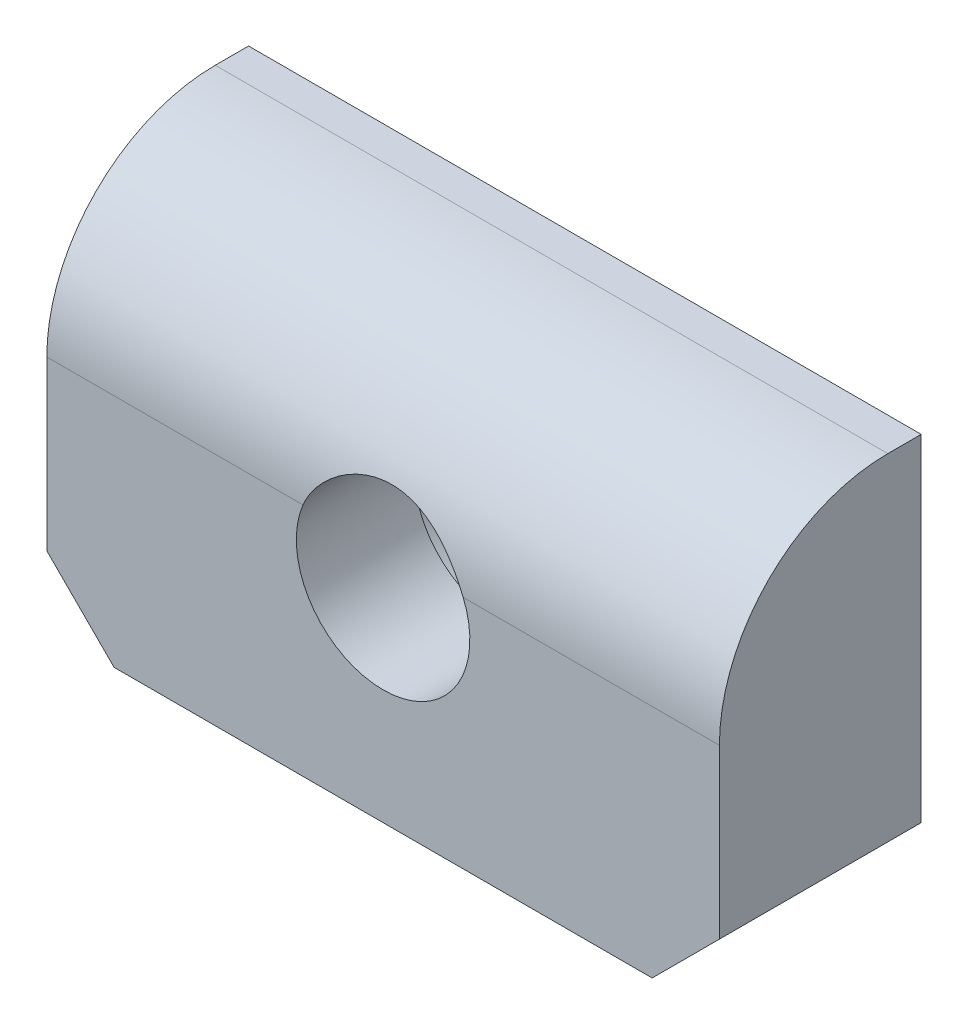
SolidWorks part; units mm, degrees
material "ASTM A36 Steel"
ref_plane "Front Plane" through (0, 0, 0) normal (0, 0, 1) x (1, 0, 0)
ref_plane "Top Plane" through (0, 0, 0) normal (0, 1, 0) x (1, 0, 0)
ref_plane "Right Plane" through (0, 0, 0) normal (1, 0, 0) x (0, 0, -1)
sketch "Sketch3" plane through (0, 0, 0) normal (1, 0, 0) x (0, 0, -1)
  line L0 (-4.7625, 1.5748) -> (-4.7625, -9.525)
  line L1 (-4.7625, -9.525) -> (4.7625, -9.525)
  line L4 (4.7625, 9.525) -> (3.1877, 9.525)
  line L6 (4.7625, 9.525) -> (4.7625, -9.525)
  line L7 (-4.7625, 0) -> (4.7625, 0) construction
  line L8 (0, -9.525) -> (0, 9.525) construction
  arc A0 (3.1877, 9.525) -> (-4.7625, 1.5748) centre (3.1877, 1.5748) ccw
  point P0 (4.7625, -9.2194)
  dimension "D1" = 9.525
  dimension "D5" = 7.9502
  dimension "D6" = 19.05
extrude "Boss-Extrude2" add sketch "Sketch3" along normal mid plane 31.75 contours L0 L1 L4
chamfer "Chamfer1" distance 3.175 angle 45 2 edges at (-15.875, -9.525, 0) (15.875, -9.525, 0)
sketch "Sketch4" plane through (0, 0, 0) normal (1, 0, 0) x (0, 0, -1)
  line L0 (-4.7625, 4.0957) -> (0.8001, 4.0957)
  line L1 (4.7625, -9.525) -> (-4.7625, -9.525) construction
  line L2 (0.8001, 4.0957) -> (0.8001, 5.6769)
  line L3 (0.8001, 5.6769) -> (4.7625, 5.6769)
  line L4 (4.7625, 5.6769) -> (4.7625, 0)
  line L6 (-4.7625, 0) -> (-4.7625, 4.0957)
  line L7 (-4.7625, 0) -> (4.7625, 0)
  line L8 (4.7625, -6.35) -> (4.7625, 9.525) construction
  line L9 (4.7625, 0) -> (4.7625, -5.6769) construction
  line L10 (4.7625, -6.35) -> (4.7625, -9.525) construction
  line L11 (-4.7625, 0) -> (-4.7625, -4.0958) construction
  line L12 (-4.7625, 1.5748) -> (-4.7625, -6.35) construction
  point P2 (4.7625, 5.6769)
  point P4 (-4.7625, -6.35)
  point P11 (4.7625, 0)
  point P12 (0, 0)
  point P17 (4.7625, -6.35)
  point P21 (-4.7625, -6.35)
  point P22 (-4.7625, -9.525)
  point P23 (-4.7625, -9.525)
  point P24 (-4.7625, -6.35)
  point P25 (4.7625, -6.35)
  point P26 (-4.7625, -6.35)
  point P27 (4.7625, -9.525)
  point P28 (4.7625, -6.35)
  point P29 (4.7625, -6.35)
  point P30 (4.7625, -9.525)
  point P31 (-4.7625, -9.525)
  point P32 (4.7625, -9.525)
  point P33 (4.7625, -9.525)
  point P34 (-4.7625, -9.525)
  point P35 (-4.7625, 1.5748)
  point P36 (-4.7625, -6.35)
  point P37 (4.7625, 9.525)
  point P38 (3.1877, 9.525)
  point P39 (4.7625, -6.35)
  point P40 (4.7625, 9.525)
  point P41 (-4.7625, 1.5748)
  point P42 (-4.7625, -6.35)
  point P43 (4.7625, 9.525)
  point P44 (3.1877, 9.525)
  point P45 (4.7625, -6.35)
  point P46 (4.7625, 9.525)
  point P47 (-4.7625, 1.5748)
  point P48 (-4.7625, -9.525)
  point P49 (-4.7625, -9.525)
  point P50 (4.7625, -9.525)
  point P51 (4.7625, 9.525)
  point P52 (3.1877, 9.525)
  point P53 (4.7625, 9.525)
  point P54 (4.7625, -9.525)
  point P55 (-4.7625, 0)
  point P56 (4.7625, 0)
  point P57 (0, -9.525)
  point P58 (0, 9.525)
  point P59 (0, 10.4775)
  point P60 (0, -10.4775)
  point P61 (5.2388, 0)
  point P62 (-5.2388, 0)
  dimension "D2" = 4.0957
  dimension "D3" = 5.6769
  dimension "D4" = 9.525
  dimension "D5" = 3.9624
revolve "Cut-Revolve2" cut sketch "Sketch4" angle 360 about L7
